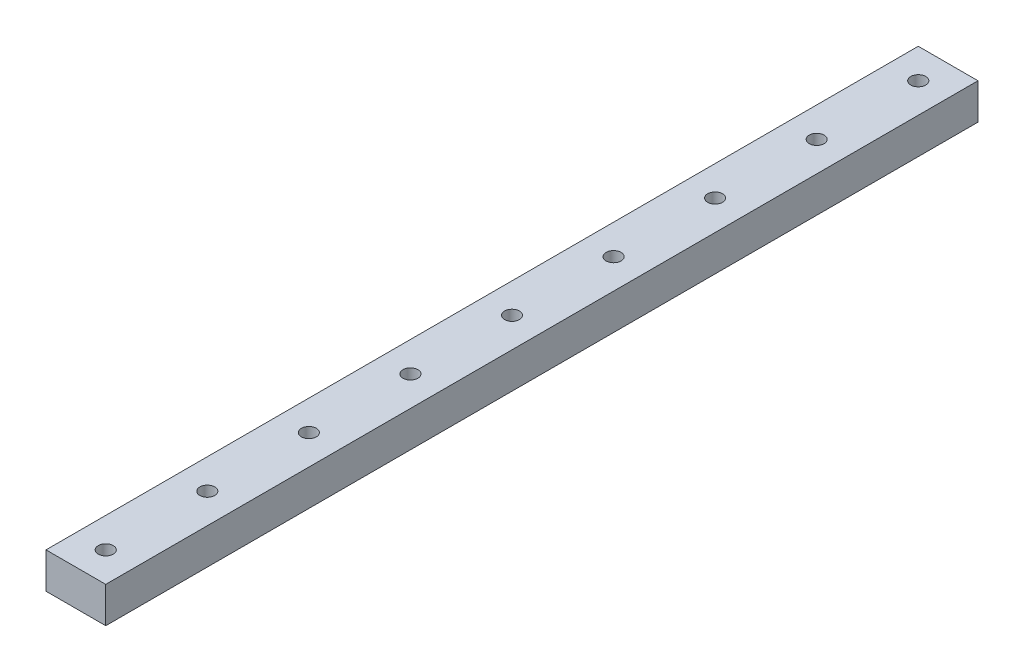
SolidWorks part; units mm, degrees
ref_plane "Front Plane" through (0, 0, 0) normal (0, 0, 1) x (1, 0, 0)
ref_plane "Top Plane" through (0, 0, 0) normal (0, 1, 0) x (1, 0, 0)
ref_plane "Right Plane" through (0, 0, 0) normal (1, 0, 0) x (0, 0, -1)
sketch "Sketch1" plane through (0, 0, 0) normal (0, 1, 0) x (1, 0, 0)
  line L1 (-5, -73) -> (5, -73)
  line L2 (-5, -73) -> (-5, 73)
  line L3 (-5, 73) -> (5, 73)
  line L4 (5, -73) -> (5, 73)
  line L5 (-5, -73) -> (5, 73) construction
  line L6 (-5, 73) -> (5, -73) construction
  point P0 (0, 0)
  dimension "D1" = 10
  dimension "D2" = 146
extrude "Boss-Extrude1" add sketch "Sketch1" along normal blind 6
sketch "Sketch2" plane through (0, 6, 0) normal (0, 1, 0) x (1, 0, 0)
  line L0 (-5, 68) -> (5, 68) construction
  line L1 (-5, 73) -> (-5, -73) construction
  line L2 (5, -73) -> (5, 73) construction
  line L3 (5, 73) -> (-5, 73) construction
  circle A0 centre (0, 68) radius 1.25
  point P8 (0, 0)
  dimension "D1" = 2.5
  dimension "D2" = 5
extrude "Cut-Extrude1" cut sketch "Sketch2" against normal up to next
pattern_linear "LPattern1" count 9 spacing 17 along (0, 0, 1) of "Cut-Extrude1"
